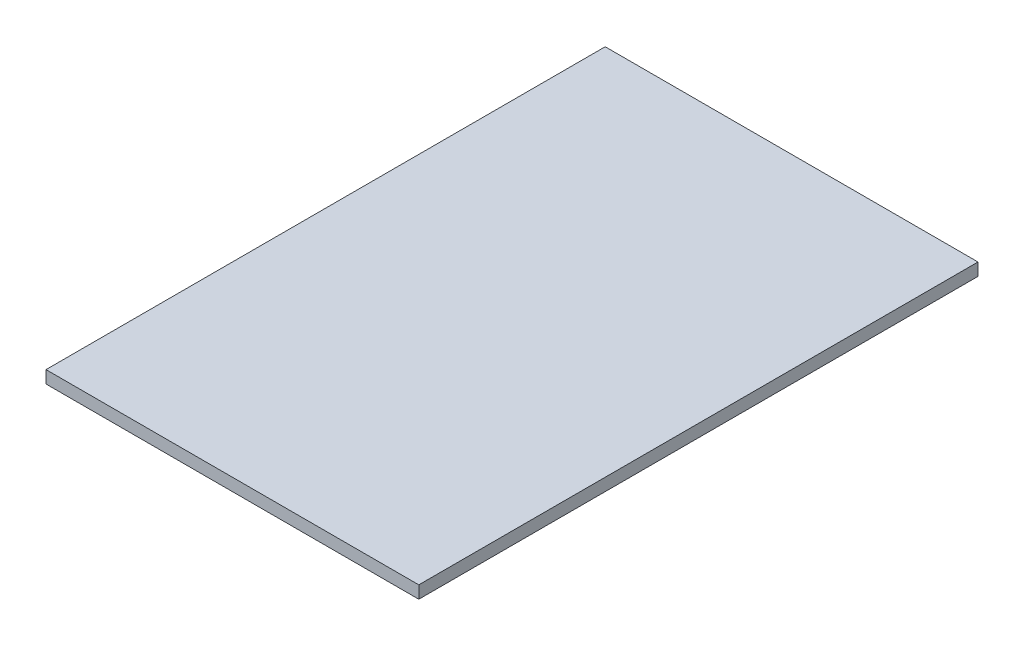
SolidWorks part; units mm, degrees
ref_plane "Front Plane" through (0, 0, 0) normal (0, 0, 1) x (1, 0, 0)
ref_plane "Top Plane" through (0, 0, 0) normal (0, 1, 0) x (1, 0, 0)
ref_plane "Right Plane" through (0, 0, 0) normal (1, 0, 0) x (0, 0, -1)
sketch "Sketch1" plane through (0, 0, 0) normal (0, 1, 0) x (1, 0, 0)
  line L1 (0, 0) -> (200, 0)
  line L2 (0, 0) -> (0, 300)
  line L3 (0, 300) -> (200, 300)
  line L4 (200, 0) -> (200, 300)
  line L5 (0, 0) -> (200, 300) construction
  line L6 (0, 300) -> (200, 0) construction
  point P4 (100, 150)
  dimension "D1" = 200
  dimension "D2" = 300
extrude "Boss-Extrude1" add sketch "Sketch1" along normal blind 6.7
